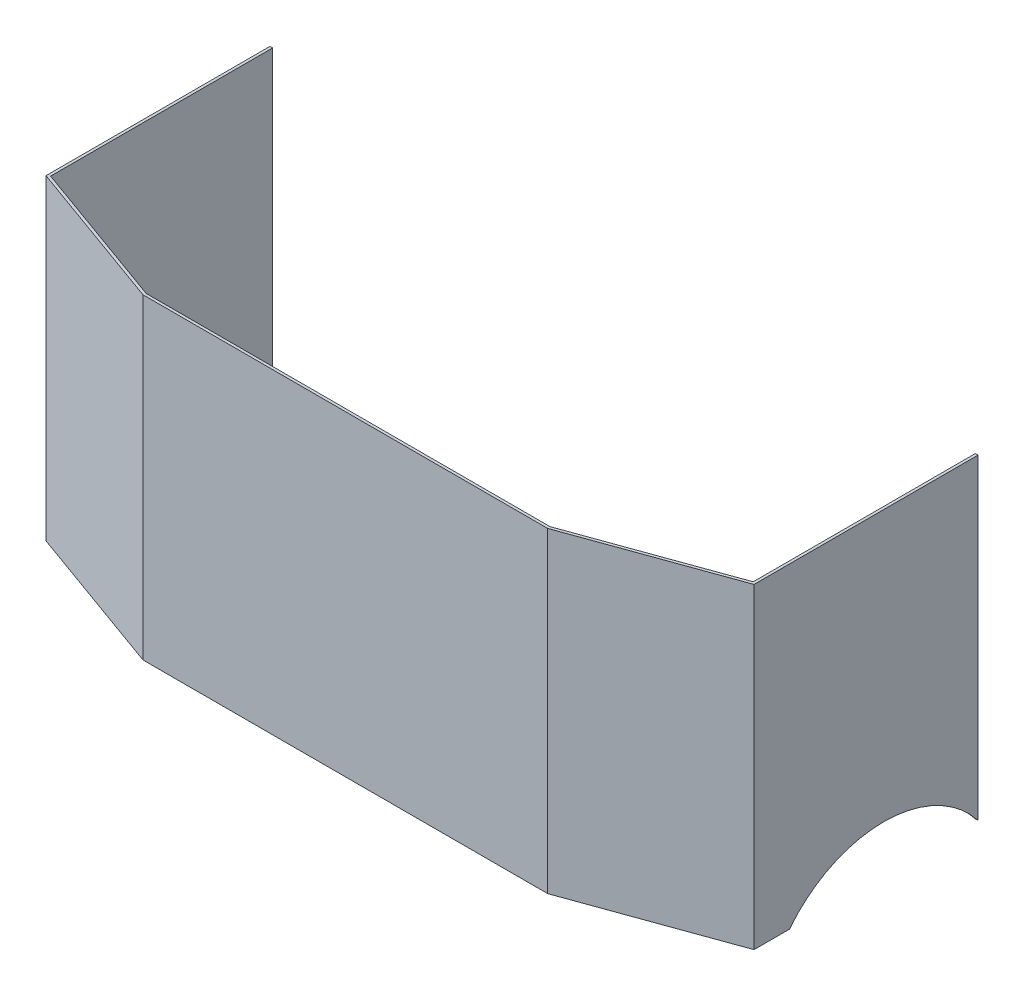
SolidWorks part; units mm, degrees
ref_plane "Front Plane" through (0, 0, 0) normal (0, 0, 1) x (1, 0, 0)
ref_plane "Top Plane" through (0, 0, 0) normal (0, 1, 0) x (1, 0, 0)
ref_plane "Right Plane" through (0, 0, 0) normal (1, 0, 0) x (0, 0, -1)
sketch "Sketch2" plane through (0, 0, 0) normal (0, 1, 0) x (1, 0, 0)
  line L0 (-263, 45.0012) -> (-263, -121.4052)
  line L1 (-263, -121.4052) -> (-150.3494, -162)
  line L2 (-150.3494, -162) -> (150.3494, -162)
  line L3 (150.3494, -162) -> (263, -121.4052)
  line L4 (263, -121.4052) -> (263, 45.0035)
  line L6 (-263, 45.0012) -> (-261, 45.0012)
  line L7 (-261, -120) -> (-150, -160)
  line L8 (-150, -160) -> (150, -160)
  line L9 (150, -160) -> (261, -120)
  line L10 (261, -120) -> (261, 45.0035)
  line L11 (263, 45.0035) -> (261, 45.0035)
  line L12 (-261, -120) -> (-261, 45.0012)
extrude "Boss-Extrude2" add sketch "Sketch2" along normal blind 235
sketch "Sketch3" plane through (-263, 0, 0) normal (-1, 0, 0) x (0, 0, 1)
  line L0 (-28.0331, 0) -> (95.0012, 0) construction
  line L1 (-45.0012, 0) -> (121.4052, 0) construction
  line L2 (-36.0916, 0) -> (117.6174, 0) construction
  circle A2 centre (25, -54.8) radius 88.9
  dimension "D2" = 177.8
  dimension "D1" = 26.404
extrude "Cut-Extrude1" cut sketch "Sketch3" against normal up to surface (526 mm away) up to face at (263, 117.5, 38.2009)
equation "\"gap\"= 1mm"
equation "\"casewidth\"= 2mm"
equation "\"flatheight\"= 235mm"
equation "\"D1@Boss-Extrude2\"=\"flatheight\""
